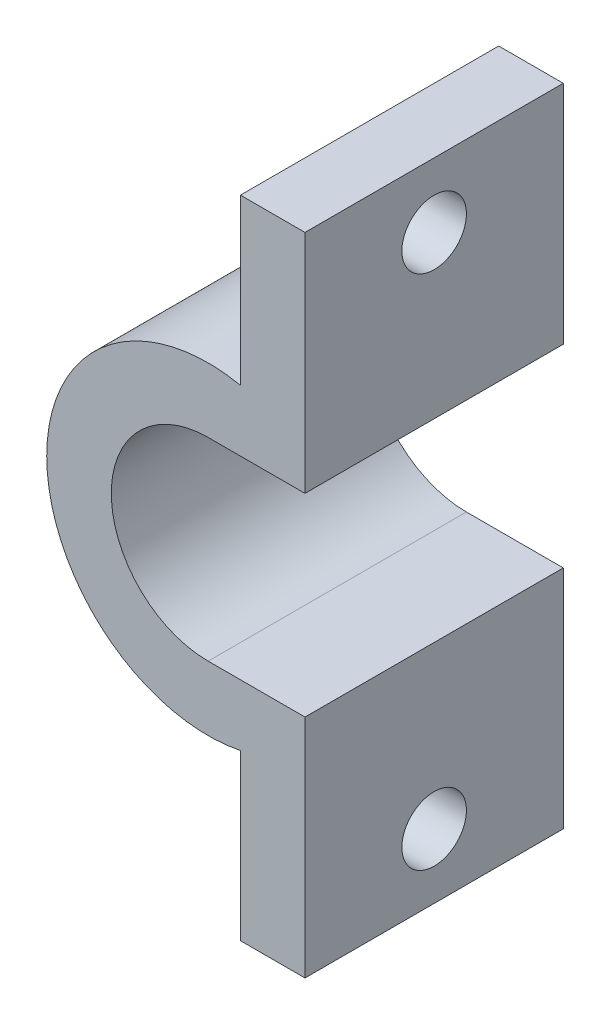
SolidWorks part; units mm, degrees
ref_plane "Front Plane" through (0, 0, 0) normal (0, 0, 1) x (1, 0, 0)
ref_plane "Top Plane" through (0, 0, 0) normal (0, 1, 0) x (1, 0, 0)
ref_plane "Right Plane" through (0, 0, 0) normal (1, 0, 0) x (0, 0, -1)
sketch "Sketch1" plane through (0, 0, 0) normal (0, 0, 1) x (1, 0, 0)
  line L0 (0, 62.1551) -> (0, 7.5) construction
  line L1 (-5, -25) -> (-5, -12.2474)
  line L3 (-5, 12.2474) -> (-5, 25)
  line L4 (-5, -25) -> (0, -25)
  line L5 (0, -25) -> (0, -7.5)
  line L6 (0, 25) -> (-5, 25)
  line L7 (-7.5, 7.5) -> (0, 7.5)
  line L8 (-7.5, -7.5) -> (0, -7.5)
  line L9 (0, -7.5) -> (0, -53.6327) construction
  line L10 (0, 7.5) -> (0, 25)
  arc A2 (-7.5, 7.5) -> (-7.5, -7.5) centre (-7.5, 0) ccw
  arc A4 (-5, 12.2474) -> (-5, -12.2474) centre (-7.5, 0) ccw
  arc A5 (-7.5, 7.5) -> (-7.5, -7.5) centre (-7.5, 0) ccw
  dimension "D1" = 15
  dimension "D2" = 5
  dimension "D4" = 25
  dimension "D5" = 12.5
  dimension "D3" = 25
  dimension "D6" = 5
extrude "Boss-Extrude1" add sketch "Sketch1" along normal blind 20 contours L3 A4 L1 L4 L5 L8 A2 L7 L10 L6
sketch "Sketch2" plane through (-5, 0, 0) normal (-1, 0, 0) x (0, 0, 1)
  line L0 (20, 25) -> (0, 25) construction
  line L1 (20, 7.5) -> (20, 25) construction
  line L2 (20, -25) -> (0, -25) construction
  line L5 (20, -25) -> (20, -7.5) construction
  circle A0 centre (10, 20) radius 2.5
  circle A1 centre (10, -20) radius 2.5
  dimension "D1" = 5
  dimension "D2" = 5
  dimension "D3" = 5
  dimension "D4" = 10
  dimension "D5" = 5
  dimension "D6" = 10
extrude "Cut-Extrude1" cut sketch "Sketch2" against normal blind 15
